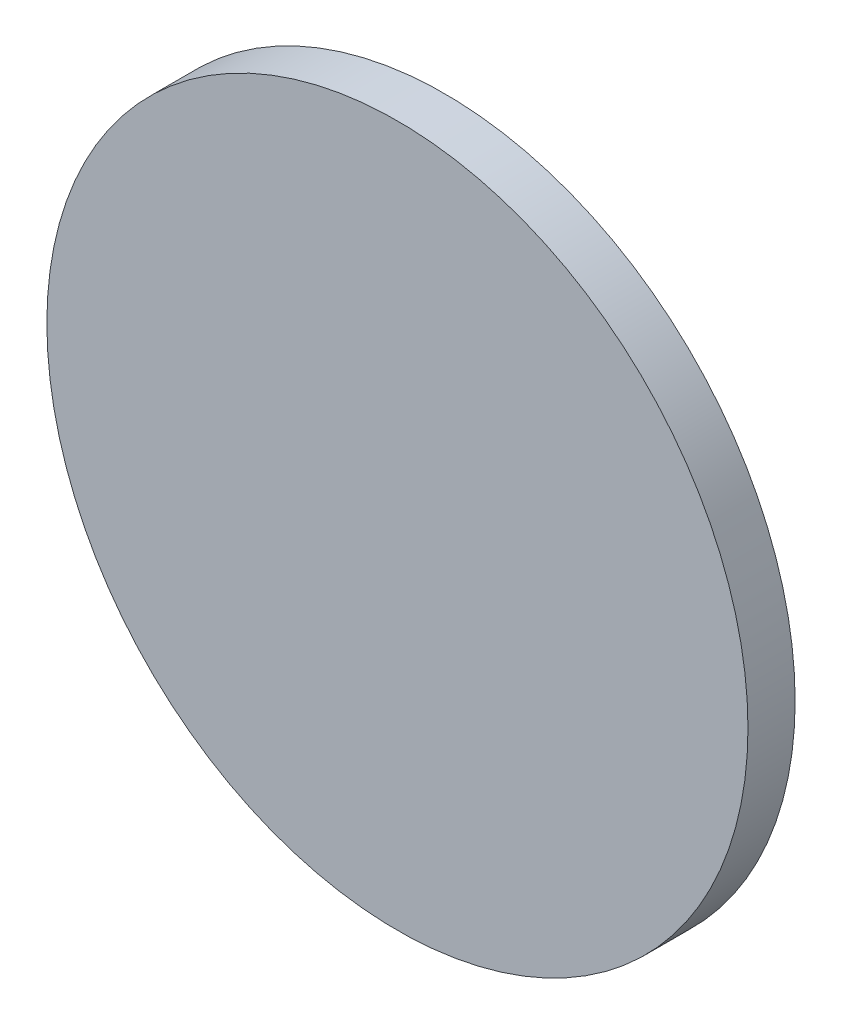
SolidWorks part; units mm, degrees
ref_plane "Front Plane" through (0, 0, 0) normal (0, 0, 1) x (1, 0, 0)
ref_plane "Top Plane" through (0, 0, 0) normal (0, 1, 0) x (1, 0, 0)
ref_plane "Right Plane" through (0, 0, 0) normal (1, 0, 0) x (0, 0, -1)
sketch "Sketch1" plane through (0, 0, 0) normal (0, 0, 1) x (1, 0, 0)
  circle A0 centre (0, 0) radius 74.3232
extrude "Boss-Extrude1" add sketch "Sketch1" along normal blind 10
